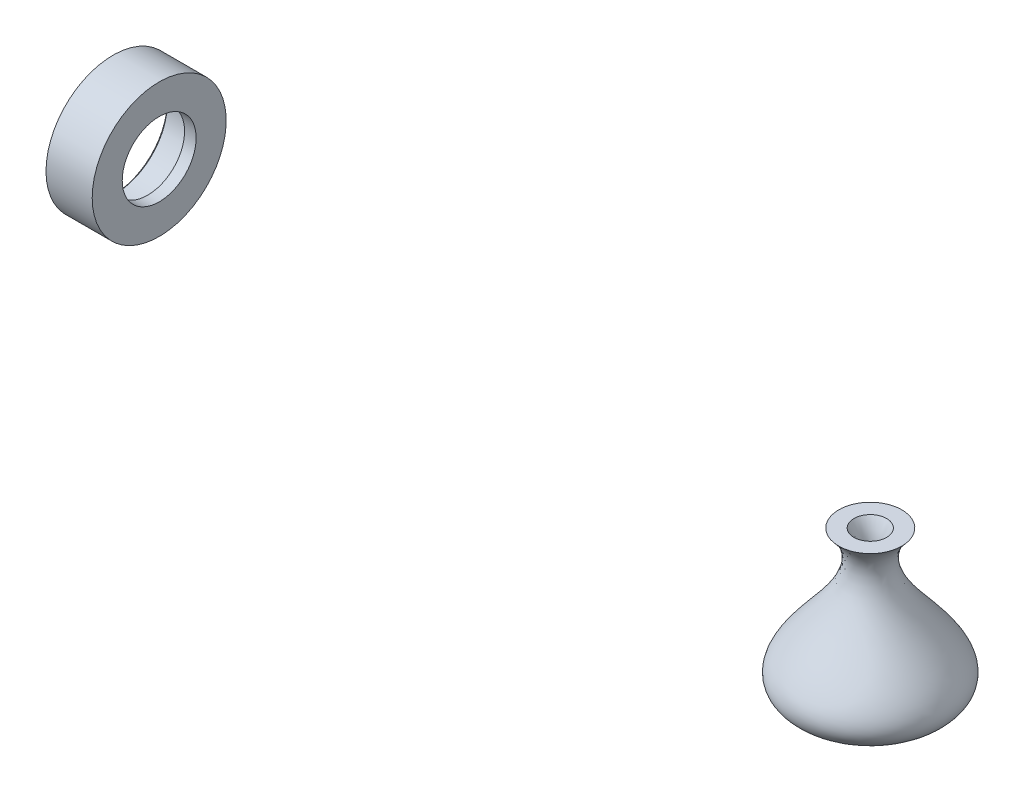
SolidWorks part; units mm, degrees
ref_plane "前视基准面" through (0, 0, 0) normal (0, 0, 1) x (1, 0, 0)
ref_plane "上视基准面" through (0, 0, 0) normal (0, 1, 0) x (1, 0, 0)
ref_plane "右视基准面" through (0, 0, 0) normal (1, 0, 0) x (0, 0, -1)
sketch "草图1" plane through (0, 0, 0) normal (0, 0, 1) x (1, 0, 0)
  line L0 (-21.775, -22.1074) -> (-12.9652, -22.1074)
  line L1 (-12.9652, -22.1074) -> (-12.9652, 45.877)
  line L2 (-26.5954, 45.877) -> (-12.9652, 45.877)
  spline S0 degree 3 poles (-26.5954, 45.877) (-0.7967, 20.5804) (-85.2462, -11.0057) (-21.775, -22.1074) knots 0 0 0 0 1 1 1 1
revolve "旋转1" add sketch "草图1" angle 360 about L1
sketch "草图2" plane through (0, 0, 0) normal (0, 0, 1) x (1, 0, 0)
  line L1 (-12.9652, -17.1074) -> (-12.9652, 45.877)
  line L2 (-21.775, -17.1074) -> (-4.1555, -17.1074)
  line L3 (-21.775, -17.1074) -> (-12.9652, -17.1074)
  line L4 (0.6649, 45.877) -> (-26.5954, 45.877) construction
  line L5 (-12.9652, 45.877) -> (-20.0509, 45.877)
  spline S3 degree 3 poles (3525.9509, 1849.32) (260.6035, -243.4355) (-32.5523, 58.7823) (-22.9922, 49.3461) (-22.9645, 49.3186) (-22.8859, 49.2403) (-22.8351, 49.1894) (-22.6798, 49.0324) (-22.5772, 48.927) (-22.2705, 48.6068) (-22.0682, 48.3888) (-21.4692, 47.7202) (-21.0802, 47.2551) (-19.9552, 45.7964) (-19.2606, 44.7376) (-18.0659, 42.4481) (-17.568, 41.2165) (-16.8519, 38.6533) (-16.6355, 37.3246) (-16.4902, 34.6922) (-16.5593, 33.3908) (-16.912, 30.8913) (-17.1937, 29.6923) (-17.8932, 27.4071) (-18.3106, 26.3197) (-19.2291, 24.2394) (-19.7305, 23.246) (-21.3133, 20.3754) (-22.4709, 18.6057) (-24.8629, 15.2306) (-26.0999, 13.6262) (-28.5886, 10.5092) (-29.8416, 8.9973) (-32.3083, 6.0192) (-33.5233, 4.553) (-35.2605, 2.3663) (-35.8251, 1.6396) (-36.9101, 0.1899) (-37.4305, -0.5332) (-38.4043, -1.9713) (-38.8578, -2.6867) (-39.6628, -4.0925) (-40.014, -4.7837) (-40.5659, -6.0934) (-40.7641, -6.7114) (-40.9249, -7.5105) (-40.9563, -7.755) (-40.9809, -8.1936) (-40.9745, -8.3873) (-40.9336, -8.7364) (-40.8998, -8.8923) (-40.8025, -9.1986) (-40.7388, -9.3499) (-40.5643, -9.6722) (-40.4531, -9.843) (-40.1707, -10.2047) (-39.9996, -10.395) (-39.3985, -10.9785) (-38.8808, -11.3818) (-37.6881, -12.1545) (-37.0147, -12.5251) (-35.5762, -13.22) (-34.8108, -13.5451) (-33.2239, -14.1528) (-32.402, -14.4357) (-29.8822, -15.2302) (-28.1315, -15.6883) (-25.457, -16.3) (-24.5568, -16.4911) (-23.1971, -16.7618) (-22.7423, -16.8493) (-22.0579, -16.9769) (-21.8295, -17.0188) (-21.4863, -17.0807) (-21.3721, -17.1012) (-12.9607, -18.5959) (-21.0803, -16.0761) (3908.7041, -759.9585) knots -0.354937 -0.354937 -0.354937 -0.354937 0.000977 0.000977 0.001953 0.001953 0.003906 0.003906 0.007813 0.007813 0.015625 0.015625 0.03125 0.03125 0.0625 0.0625 0.09375 0.09375 0.125 0.125 0.15625 0.15625 0.1875 0.1875 0.21875 0.21875 0.25 0.25 0.3125 0.3125 0.375 0.375 0.4375 0.4375 0.5 0.5 0.53125 0.53125 0.5625 0.5625 0.59375 0.59375 0.625 0.625 0.65625 0.65625 0.671875 0.671875 0.6875 0.6875 0.703125 0.703125 0.71875 0.71875 0.734375 0.734375 0.75 0.75 0.78125 0.78125 0.8125 0.8125 0.84375 0.84375 0.875 0.875 0.9375 0.9375 0.96875 0.96875 0.984375 0.984375 0.992188 0.992188 0.996094 0.996094 1.278271 1.278271 1.278271 1.278271 only from (-23.09, 49.4424) to (-20.9116, -17.1825)
  spline S4 degree 3 poles (-20.0509, 45.877) (-19.5501, 45.1581) (-19.0827, 44.3967) (-18.0659, 42.4481) (-17.568, 41.2165) (-16.8519, 38.6533) (-16.6355, 37.3246) (-16.4902, 34.6922) (-16.5593, 33.3908) (-16.912, 30.8913) (-17.1937, 29.6923) (-17.8932, 27.4071) (-18.3106, 26.3197) (-19.2291, 24.2394) (-19.7305, 23.246) (-21.3133, 20.3754) (-22.4709, 18.6057) (-24.8629, 15.2306) (-26.0999, 13.6262) (-28.5886, 10.5092) (-29.8416, 8.9973) (-32.3083, 6.0192) (-33.5233, 4.553) (-35.2605, 2.3663) (-35.8251, 1.6396) (-36.9101, 0.1899) (-37.4305, -0.5332) (-38.4043, -1.9713) (-38.8578, -2.6867) (-39.6628, -4.0925) (-40.014, -4.7837) (-40.5659, -6.0934) (-40.7641, -6.7114) (-40.9249, -7.5105) (-40.9563, -7.755) (-40.9809, -8.1936) (-40.9745, -8.3873) (-40.9336, -8.7364) (-40.8998, -8.8923) (-40.8025, -9.1986) (-40.7388, -9.3499) (-40.5643, -9.6722) (-40.4531, -9.843) (-40.1707, -10.2047) (-39.9996, -10.395) (-39.3985, -10.9785) (-38.8808, -11.3818) (-37.6881, -12.1545) (-37.0147, -12.5251) (-35.5762, -13.22) (-34.8108, -13.5451) (-33.2239, -14.1528) (-32.402, -14.4357) (-29.8822, -15.2302) (-28.1315, -15.6883) (-25.457, -16.3) (-24.5568, -16.4911) (-23.1971, -16.7618) (-22.7423, -16.8493) (-22.0579, -16.9769) (-21.8295, -17.0188) (-21.4863, -17.0807) (-21.3721, -17.1012) (-21.1424, -17.142) (-21.0307, -17.1616) (-20.9116, -17.1825) knots 0.040557 0.040557 0.040557 0.040557 0.0625 0.0625 0.09375 0.09375 0.125 0.125 0.15625 0.15625 0.1875 0.1875 0.21875 0.21875 0.25 0.25 0.3125 0.3125 0.375 0.375 0.4375 0.4375 0.5 0.5 0.53125 0.53125 0.5625 0.5625 0.59375 0.59375 0.625 0.625 0.65625 0.65625 0.671875 0.671875 0.6875 0.6875 0.703125 0.703125 0.71875 0.71875 0.734375 0.734375 0.75 0.75 0.78125 0.78125 0.8125 0.8125 0.84375 0.84375 0.875 0.875 0.9375 0.9375 0.96875 0.96875 0.984375 0.984375 0.992188 0.992188 0.996094 0.996094 1 1 1 1
  dimension "D1" = 5
  dimension "D2" = 5
revolve "切除-旋转1" cut sketch "草图2" angle 360 about L1
sketch "草图3" plane through (0, 0, 0) normal (0, 0, 1) x (1, 0, 0)
  line L0 (-386.4103, 30.1997) -> (-219.0458, 30.1997) construction
  line L1 (-325.8051, 55.1997) -> (-325.8051, 46.1997)
  line L2 (-340.8051, 30.1997) -> (-320.8051, 30.1997)
  line L3 (-340.8051, 52.6997) -> (-340.8051, 59.1997)
  line L4 (-340.8051, 59.1997) -> (-320.8051, 59.1997)
  line L5 (-320.8051, 46.1997) -> (-320.8051, 59.1997)
  line L6 (-325.8051, 46.1997) -> (-320.8051, 46.1997)
  line L7 (-328.8051, 55.1997) -> (-325.8051, 55.1997)
  line L8 (-340.8051, 52.6997) -> (-328.8051, 52.6997)
  line L9 (-328.8051, 52.6997) -> (-328.8051, 55.1997)
  dimension "D1" = 29
  dimension "D2" = 16
  dimension "D3" = 5
  dimension "D4" = 25
  dimension "D5" = 22.5
  dimension "D6" = 20
  dimension "D7" = 3
revolve "旋转2" add sketch "草图3" angle 360 about L0
cosmetic thread "装饰螺纹线1" parameters "D2"=135
cosmetic thread "装饰螺纹线2" parameters "D1"=5, "D2"=135
chamfer "倒角1" distance 1 angle 45 1 edges at (-340.8051, 30.1997, 22.5)
